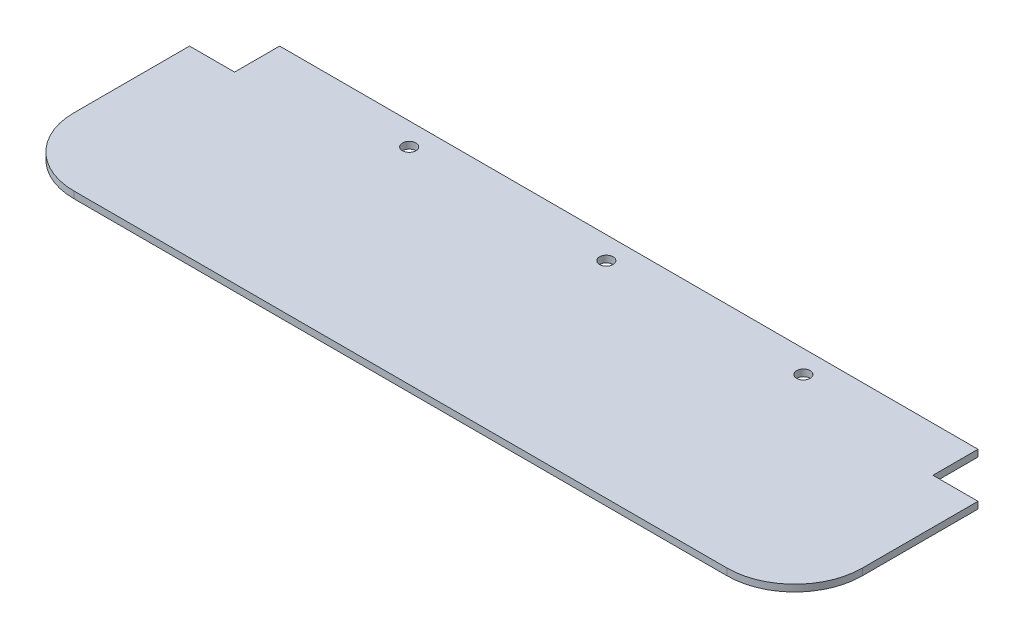
SolidWorks part; units mm, degrees
ref_plane "前基準面" through (0, 0, 0) normal (0, 0, 1) x (1, 0, 0)
ref_plane "上基準面" through (0, 0, 0) normal (0, 1, 0) x (1, 0, 0)
ref_plane "右基準面" through (0, 0, 0) normal (1, 0, 0) x (0, 0, -1)
sketch "草圖1" plane through (0, 0, 0) normal (0, 1, 0) x (1, 0, 0)
  line L1 (-175, -50.685) -> (175, -50.685)
  line L2 (-175, -50.685) -> (-175, 50.685)
  line L3 (-175, 50.685) -> (175, 50.685)
  line L4 (175, -50.685) -> (175, 50.685)
  line L5 (-175, -50.685) -> (175, 50.685) construction
  line L6 (-175, 50.685) -> (175, -50.685) construction
  point P0 (0, 0)
  dimension "D1" = 350
  dimension "D2" = 101.37
extrude "填料-伸長1" add sketch "草圖1" along normal blind 3
sketch "草圖2" plane through (0, 3, 0) normal (0, 1, 0) x (1, 0, 0)
  line L1 (-175, 50.685) -> (-155, 50.685)
  line L2 (-175, 50.685) -> (-175, 30.685)
  line L3 (-175, 30.685) -> (-155, 30.685)
  line L4 (-155, 50.685) -> (-155, 30.685)
  line L5 (0, -1.65) -> (0, 1.65) construction
  line L10 (155, 50.685) -> (155, 30.685)
  line L11 (175, 30.685) -> (155, 30.685)
  line L12 (175, 50.685) -> (175, 30.685)
  line L13 (175, 50.685) -> (155, 50.685)
  line L14 (175, 50.685) -> (-175, 50.685) construction
  circle A0 centre (-87.5, 40.685) radius 3
  circle A1 centre (0, 40.685) radius 3
  circle A2 centre (87.5, 40.685) radius 3
  point P20 (0, 0)
  dimension "D3" = 6
  dimension "D6" = 6
  dimension "D7" = 6
  dimension "D1" = 20
  dimension "D2" = 20
  dimension "D4" = 10
  dimension "D5" = 87.5
  dimension "D8" = 87.5
extrude "除料-伸長1" cut sketch "草圖2" against normal through all
fillet "圓角1" radius 30 2 edges at (175, 1.5, 50.685) (-175, 1.5, 50.685)
